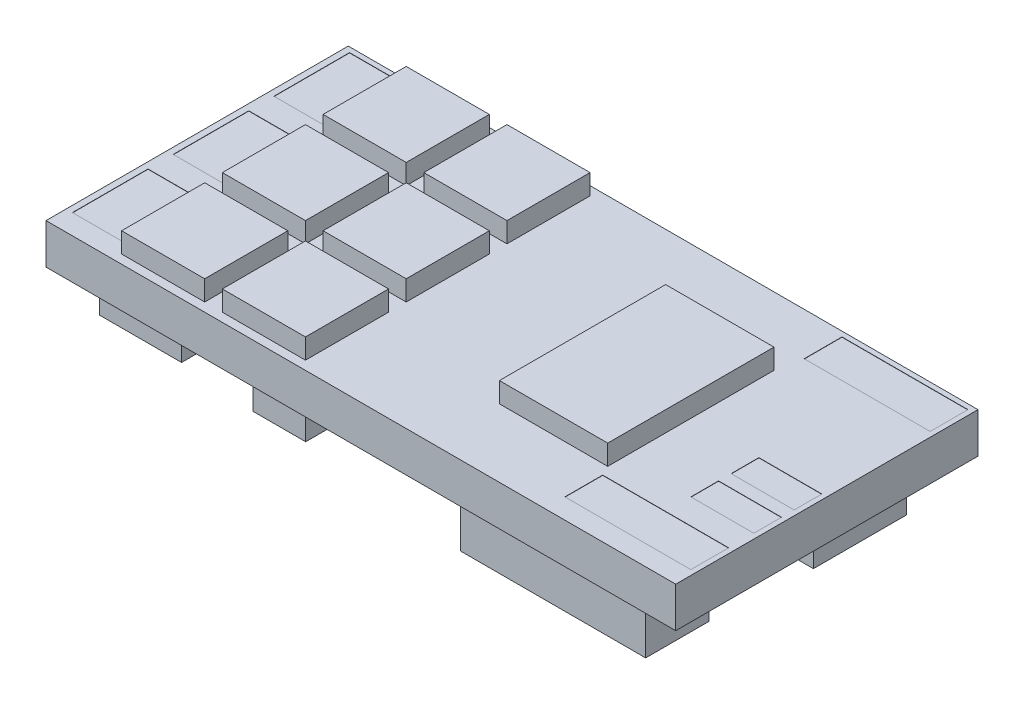
SolidWorks part; units mm, degrees
ref_plane "Front Plane" through (0, 0, 0) normal (0, 0, 1) x (1, 0, 0)
ref_plane "Top Plane" through (0, 0, 0) normal (0, 1, 0) x (1, 0, 0)
ref_plane "Right Plane" through (0, 0, 0) normal (1, 0, 0) x (0, 0, -1)
sketch "Sketch1" plane through (0, 0, 0) normal (0, 1, 0) x (1, 0, 0)
  line L1 (-12.5, 6) -> (12.5, 6)
  line L2 (-12.5, 6) -> (-12.5, -6)
  line L3 (-12.5, -6) -> (12.5, -6)
  line L4 (12.5, 6) -> (12.5, -6)
  line L5 (-12.5, 6) -> (12.5, -6) construction
  line L6 (-12.5, -6) -> (12.5, 6) construction
  point P0 (0, 0)
  dimension "D1" = 12
  dimension "D2" = 25
extrude "Boss-Extrude1" add sketch "Sketch1" along normal blind 1.6
sketch "Sketch2" plane through (0, 1.6, 0) normal (0, 1, 0) x (1, 0, 0)
  line L0 (-12.5, 0) -> (12.5, 0) construction
  line L1 (-12.5, 6) -> (-12.5, -6) construction
  line L2 (12.5, -6) -> (12.5, 6) construction
  line L3 (-12.5, 4) -> (12.5, 4) construction
  line L4 (-5.85, 5.65) -> (-5.85, 2.35)
  line L5 (-9.85, -2.35) -> (-6.55, -2.35)
  line L6 (12.5, 6) -> (-12.5, 6) construction
  line L7 (-12.5, -4) -> (12.5, -4) construction
  line L8 (-8.2, 6) -> (-8.2, -6) construction
  line L9 (-9.85, 5.65) -> (-6.55, 5.65)
  line L10 (-9.85, 5.65) -> (-9.85, 2.35)
  line L11 (-9.85, 2.35) -> (-6.55, 2.35)
  line L12 (-6.55, 5.65) -> (-6.55, 2.35)
  line L13 (-9.85, 5.65) -> (-6.55, 2.35) construction
  line L14 (-9.85, 2.35) -> (-6.55, 5.65) construction
  line L15 (-9.85, 1.65) -> (-6.55, 1.65)
  line L16 (-9.85, 1.65) -> (-9.85, -1.65)
  line L17 (-9.85, -1.65) -> (-6.55, -1.65)
  line L18 (-6.55, 1.65) -> (-6.55, -1.65)
  line L19 (-9.85, 1.65) -> (-6.55, -1.65) construction
  line L20 (-9.85, -1.65) -> (-6.55, 1.65) construction
  line L21 (-12.5, -6) -> (12.5, -6) construction
  line L22 (-9.85, -2.35) -> (-9.85, -5.65)
  line L23 (-9.85, -5.65) -> (-6.55, -5.65)
  line L24 (-6.55, -2.35) -> (-6.55, -5.65)
  line L25 (-9.85, -2.35) -> (-6.55, -5.65) construction
  line L26 (-9.85, -5.65) -> (-6.55, -2.35) construction
  line L27 (-5.85, 5.65) -> (-2.55, 5.65)
  line L28 (-2.55, 5.65) -> (-2.55, 2.35)
  line L29 (-5.85, 2.35) -> (-2.55, 2.35)
  line L30 (-5.85, 1.65) -> (-2.55, 1.65)
  line L31 (-5.85, 1.65) -> (-5.85, -1.65)
  line L32 (-5.85, -1.65) -> (-2.55, -1.65)
  line L33 (-2.55, 1.65) -> (-2.55, -1.65)
  line L34 (-5.85, -2.35) -> (-2.55, -2.35)
  line L35 (-5.85, -2.35) -> (-5.85, -5.65)
  line L36 (-5.85, -5.65) -> (-2.55, -5.65)
  line L37 (-2.55, -2.35) -> (-2.55, -5.65)
  line L38 (-5.85, 0) -> (-2.55, 0) construction
  line L39 (-4.2, 1.65) -> (-4.2, -1.65) construction
  line L41 (2.8, 3.3) -> (7.1, 3.3)
  line L42 (2.8, 3.3) -> (2.8, -3.3)
  line L43 (2.8, -3.3) -> (7.1, -3.3)
  line L44 (7.1, 3.3) -> (7.1, -3.3)
  line L45 (2.8, 3.3) -> (7.1, -3.3) construction
  line L46 (2.8, -3.3) -> (7.1, 3.3) construction
  point P8 (-8.2, -4)
  point P16 (-8.2, 4)
  point P21 (-8.2, 0)
  point P47 (4.95, 0)
  dimension "D1" = 3.3
  dimension "D2" = 3.3
  dimension "D3" = 4.3
  dimension "D4" = 2
  dimension "D6" = 4
  dimension "D7" = 4.3
  dimension "D8" = 6.6
  dimension "D9" = 5.4
  dimension "D5" = 2
extrude "Boss-Extrude2" add sketch "Sketch2" along normal blind 0.8
sketch "Sketch3" plane through (0, 1.6, 0) normal (0, 1, 0) x (1, 0, 0)
  line L0 (-12.5, 0.3) -> (12.5, 0.3) construction
  line L1 (-12.5, 6) -> (-12.5, -6) construction
  line L2 (12.5, -6) -> (12.5, 6) construction
  line L3 (-12.5, 4.3) -> (12.5, 4.3) construction
  line L4 (-12.5, -3.7) -> (12.5, -3.7) construction
  line L5 (12.5, 6) -> (-12.5, 6) construction
  line L6 (-12.25, 5.8) -> (-10.25, 5.8)
  line L7 (-12.25, 5.8) -> (-12.25, 2.8)
  line L8 (-12.25, 2.8) -> (-10.25, 2.8)
  line L9 (-10.25, 5.8) -> (-10.25, 2.8)
  line L10 (-12.25, 5.8) -> (-10.25, 2.8) construction
  line L11 (-12.25, 2.8) -> (-10.25, 5.8) construction
  line L12 (-11.25, 6) -> (-11.25, -6) construction
  line L13 (-12.5, -6) -> (12.5, -6) construction
  line L14 (12.3, -5.2) -> (7.3, -5.2)
  line L15 (-12.25, 1.8) -> (-10.25, 1.8)
  line L16 (-12.25, 1.8) -> (-12.25, -1.2)
  line L17 (-12.25, -1.2) -> (-10.25, -1.2)
  line L18 (-10.25, 1.8) -> (-10.25, -1.2)
  line L19 (-12.25, 1.8) -> (-10.25, -1.2) construction
  line L20 (-12.25, -1.2) -> (-10.25, 1.8) construction
  line L21 (-12.25, -2.2) -> (-10.25, -2.2)
  line L22 (-12.25, -2.2) -> (-12.25, -5.2)
  line L23 (-12.25, -5.2) -> (-10.25, -5.2)
  line L24 (-10.25, -2.2) -> (-10.25, -5.2)
  line L25 (-12.25, -2.2) -> (-10.25, -5.2) construction
  line L26 (-12.25, -5.2) -> (-10.25, -2.2) construction
  line L27 (12.3, 5.8) -> (7.3, 5.8)
  line L28 (12.3, 5.8) -> (12.3, 4.3)
  line L29 (12.3, 4.3) -> (7.3, 4.3)
  line L30 (7.3, 5.8) -> (7.3, 4.3)
  line L31 (12.3, -5.2) -> (12.3, -3.7)
  line L32 (12.3, -3.7) -> (7.3, -3.7)
  line L33 (7.3, -5.2) -> (7.3, -3.7)
  line L35 (12.3, -2.7) -> (9.8, -2.7)
  line L36 (12.3, -2.7) -> (12.3, -1.6)
  line L37 (12.3, -1.6) -> (9.8, -1.6)
  line L38 (9.8, -2.7) -> (9.8, -1.6)
  line L39 (12.3, -1.1) -> (9.8, -1.1)
  line L40 (12.3, -1.1) -> (12.3, 0)
  line L41 (12.3, 0) -> (9.8, 0)
  line L42 (9.8, -1.1) -> (9.8, 0)
  point P10 (-11.25, 4.3)
  point P21 (-11.25, 0.3)
  point P26 (-11.25, -3.7)
  dimension "D1" = 2
  dimension "D2" = 4
  dimension "D3" = 4
  dimension "D4" = 3
  dimension "D5" = 1.25
  dimension "D6" = 1.7
  dimension "D7" = 0.2
  dimension "D8" = 0.2
  dimension "D9" = 1.5
  dimension "D10" = 5
  dimension "D11" = 1
  dimension "D12" = 0.5
  dimension "D13" = 1.1
  dimension "D14" = 2.5
  dimension "D15" = 0.2
extrude "Cut-Extrude1" cut sketch "Sketch3" against normal blind 0.01
sketch "Sketch4" plane through (0, 0, 0) normal (0, -1, 0) x (1, 0, 0)
  line L0 (-12.5, 0) -> (12.5, 0) construction
  line L1 (3.1008, -0.5645) -> (11.4017, -0.5645)
  line L2 (3.1008, -0.5645) -> (3.1008, -4.2529)
  line L3 (3.1008, -4.2529) -> (11.4017, -4.2529)
  line L4 (11.4017, -0.5645) -> (11.4017, -4.2529)
  line L5 (3.1008, -0.5645) -> (11.4017, -4.2529) construction
  line L6 (3.1008, -4.2529) -> (11.4017, -0.5645) construction
  line L7 (-11.4779, 4.8887) -> (-8.2298, 4.8887)
  line L8 (-11.4779, 4.8887) -> (-11.4779, -4.8887)
  line L9 (-11.4779, -4.8887) -> (-8.2298, -4.8887)
  line L10 (-8.2298, 4.8887) -> (-8.2298, -4.8887)
  line L11 (-11.4779, 4.8887) -> (-8.2298, -4.8887) construction
  line L12 (-11.4779, -4.8887) -> (-8.2298, 4.8887) construction
  line L13 (-5.1398, 5.15) -> (-3.0398, 5.15)
  line L14 (-5.1398, 5.15) -> (-5.1398, 3.05)
  line L15 (-5.1398, 3.05) -> (-3.0398, 3.05)
  line L16 (-3.0398, 5.15) -> (-3.0398, 3.05)
  line L17 (-5.1398, 5.15) -> (-3.0398, 3.05) construction
  line L18 (-5.1398, 3.05) -> (-3.0398, 5.15) construction
  line L19 (-5.1398, 1.05) -> (-3.0398, 1.05)
  line L20 (-5.1398, 1.05) -> (-5.1398, -1.05)
  line L21 (-5.1398, -1.05) -> (-3.0398, -1.05)
  line L22 (-3.0398, 1.05) -> (-3.0398, -1.05)
  line L23 (-5.1398, 1.05) -> (-3.0398, -1.05) construction
  line L24 (-5.1398, -1.05) -> (-3.0398, 1.05) construction
  line L25 (-5.1398, -3.05) -> (-3.0398, -3.05)
  line L26 (-5.1398, -3.05) -> (-5.1398, -5.15)
  line L27 (-5.1398, -5.15) -> (-3.0398, -5.15)
  line L28 (-3.0398, -3.05) -> (-3.0398, -5.15)
  line L29 (-5.1398, -3.05) -> (-3.0398, -5.15) construction
  line L30 (-5.1398, -5.15) -> (-3.0398, -3.05) construction
  line L31 (-12.5, -6) -> (-12.5, 6) construction
  line L32 (12.5, 6) -> (12.5, -6) construction
  line L34 (11.1403, 5.8336) -> (3.7887, 5.8336)
  line L35 (11.1403, 5.8336) -> (11.1403, 3.3245)
  line L36 (11.1403, 3.3245) -> (3.7887, 3.3245)
  line L37 (3.7887, 5.8336) -> (3.7887, 3.3245)
  point P0 (7.2512, -2.4087)
  point P5 (-9.8538, 0)
  point P10 (-4.0898, 4.1)
  point P15 (-4.0898, 0)
  point P20 (-4.0898, -4.1)
  dimension "D1" = 2.1
  dimension "D2" = 2
  dimension "D3" = 2
extrude "Boss-Extrude3" add sketch "Sketch4" along normal blind 1.7
